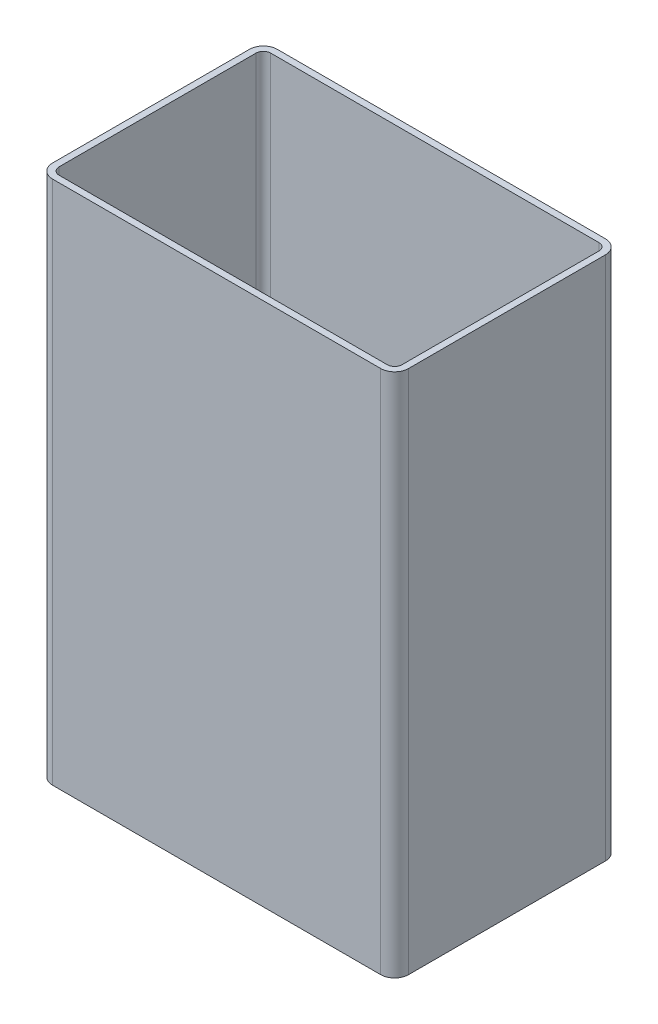
SolidWorks part; units mm, degrees
ref_plane "Front Plane" through (0, 0, 0) normal (0, 0, 1) x (1, 0, 0)
ref_plane "Top Plane" through (0, 0, 0) normal (0, 1, 0) x (1, 0, 0)
ref_plane "Right Plane" through (0, 0, 0) normal (1, 0, 0) x (0, 0, -1)
sketch "Sketch1" plane through (0, 0, 0) normal (0, 1, 0) x (1, 0, 0)
  line L0 (0, 0) -> (381, 0)
  line L1 (397.1798, 16.1798) -> (397.1798, 244.7798)
  line L2 (190.5, 0) -> (190.5, 294.1102) construction
  line L3 (397.1798, 130.4798) -> (-232.7468, 130.4798) construction
  line L4 (0, 260.9596) -> (381, 260.9596)
  line L5 (-16.1798, 16.1798) -> (-16.1798, 244.7798)
  arc A0 (381, 0) -> (397.1798, 16.1798) centre (381, 16.1798) ccw
  arc A1 (381, 260.9596) -> (397.1798, 244.7798) centre (381, 244.7798) cw
  arc A2 (0, 0) -> (-16.1798, 16.1798) centre (0, 16.1798) cw
  arc A3 (0, 260.9596) -> (-16.1798, 244.7798) centre (0, 244.7798) ccw
  dimension "D2" = 16.1798
  dimension "D1" = 381
  dimension "D3" = 228.6
extrude "Boss-Extrude1" add sketch "Sketch1" against normal blind 609.6 contours L5 A3 L4 A1 L1 A0 L0 A2
shell "Shell1" thickness 7.62
